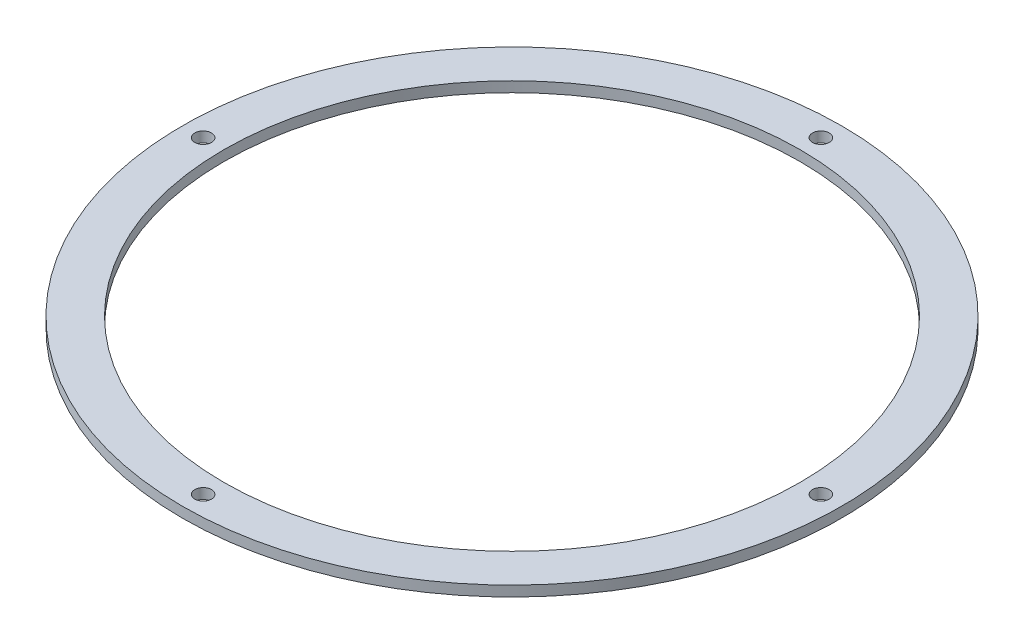
SolidWorks part; units mm, degrees
material "ABS PC"
ref_plane "Front Plane" through (0, 0, 0) normal (0, 0, 1) x (1, 0, 0)
ref_plane "Top Plane" through (0, 0, 0) normal (0, 1, 0) x (1, 0, 0)
ref_plane "Right Plane" through (0, 0, 0) normal (1, 0, 0) x (0, 0, -1)
sketch "Sketch2" plane through (0, 0, 0) normal (0, 1, 0) x (1, 0, 0)
  circle A0 centre (0, 0) radius 88.4
  circle A1 centre (0, 0) radius 94.75 construction
  circle A2 centre (0, 0) radius 101.1
  circle A3 centre (0, -94.75) radius 2.5527
  circle A4 centre (-94.75, 0) radius 2.5527
  circle A5 centre (0, 94.75) radius 2.5527
  circle A6 centre (94.75, 0) radius 2.5527
  point P16 (0, 0)
  dimension "D1" = 189.5
  dimension "D2" = 6.35
  dimension "D3" = 6.35
  dimension "D4" = 5.1054
  dimension "D5" = 4
extrude "Boss-Extrude1" add sketch "Sketch2" along normal blind 3.175
